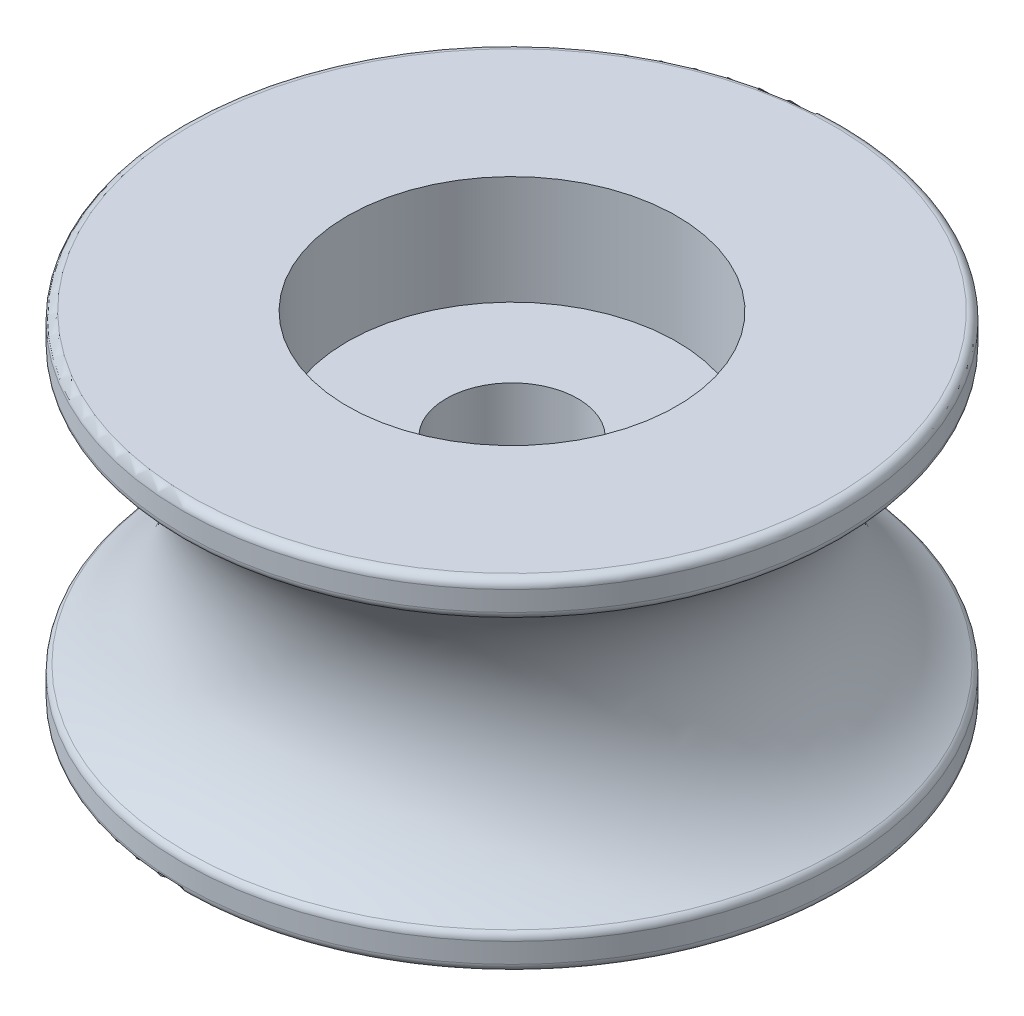
SolidWorks part; units mm, degrees
ref_plane "Piano frontale" through (0, 0, 0) normal (0, 0, 1) x (1, 0, 0)
ref_plane "Piano superiore" through (0, 0, 0) normal (0, 1, 0) x (1, 0, 0)
ref_plane "Piano destro" through (0, 0, 0) normal (1, 0, 0) x (0, 0, -1)
sketch "Schizzo5" plane through (0, 0, 0) normal (0, 0, 1) x (1, 0, 0)
  line L0 (20, 0) -> (15, 0)
  line L1 (4, 10.35) -> (20, 10.35) construction
  line L2 (4, 10.35) -> (4, -10.35) construction
  line L3 (4, -10.35) -> (20, -10.35) construction
  line L4 (20, 10.35) -> (20, -10.35) construction
  line L5 (20, 10.35) -> (20, 8.35)
  line L6 (20, -10.35) -> (20, -8.35)
  line L7 (4, 10.35) -> (0, 10.35) construction
  line L8 (0, 10.35) -> (0, -10.35) construction
  line L9 (0, -10.35) -> (4, -10.35) construction
  line L10 (4, 3.75) -> (4, -3.75)
  line L11 (10, 10.35) -> (10, 3.75)
  line L12 (10, 3.75) -> (4, 3.75)
  line L13 (10, 10.35) -> (20, 10.35)
  line L14 (10, -10.35) -> (10, -3.75)
  line L15 (10, -3.75) -> (4, -3.75)
  line L16 (10, -10.35) -> (20, -10.35)
  arc A0 (20, 8.35) -> (20, -8.35) centre (24.4661, 0) ccw
  dimension "D1" = 20.7
  dimension "D2" = 16
  dimension "D3" = 5
  dimension "D4" = 2
  dimension "D5" = 2
  dimension "D6" = 4
  dimension "D7" = 4.4661
  dimension "D8" = 6.6
  dimension "D9" = 6
  dimension "D10" = 6.6
  dimension "D11" = 6
revolve "Rivoluzione12" add sketch "Schizzo5" angle 360 about L8
fillet "Raccordo1" radius 0.5 4 edges at (-20, -10.35, 0) (-20, -8.35, 0) (-20, 10.35, 0) (-20, 8.35, 0)
